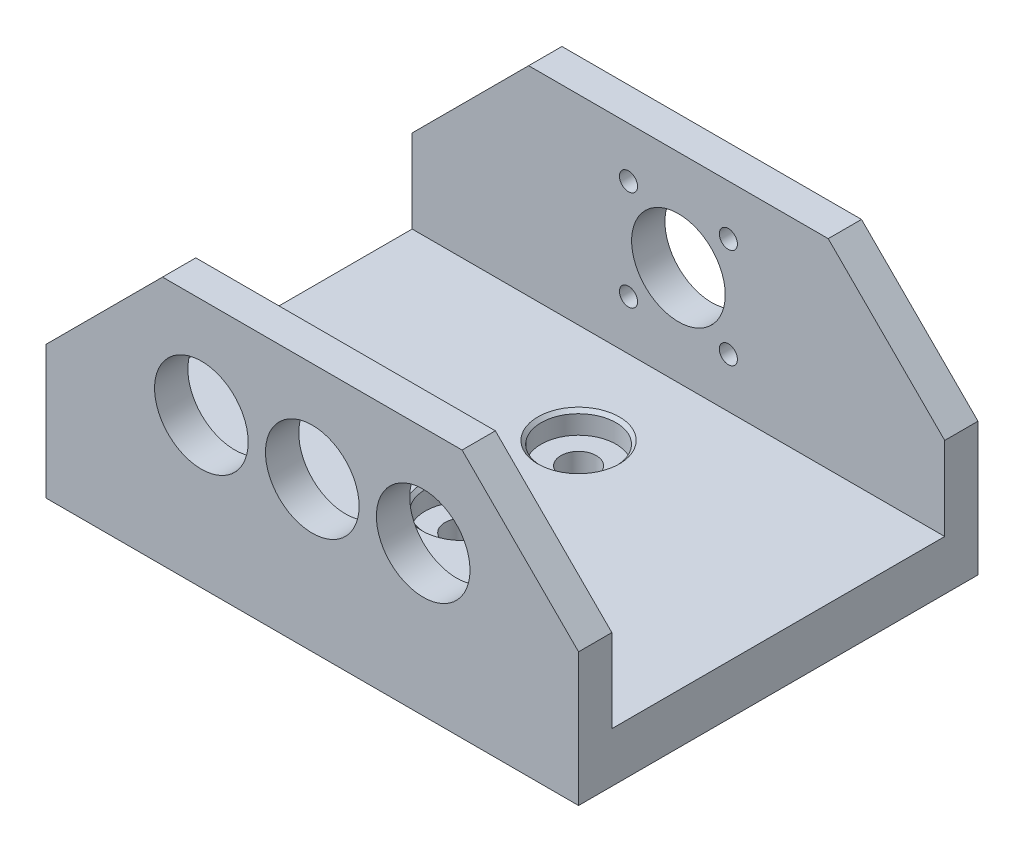
SolidWorks part; units mm, degrees
ref_plane "Front Plane" through (0, 0, 0) normal (0, 0, 1) x (1, 0, 0)
ref_plane "Top Plane" through (0, 0, 0) normal (0, 1, 0) x (1, 0, 0)
ref_plane "Right Plane" through (0, 0, 0) normal (1, 0, 0) x (0, 0, -1)
sketch "Sketch1" plane through (0, 0, 0) normal (0, 1, 0) x (1, 0, 0)
  line L1 (0, 0) -> (101.6, 0)
  line L2 (0, 0) -> (0, 76.2)
  line L3 (0, 76.2) -> (101.6, 76.2)
  line L4 (101.6, 0) -> (101.6, 76.2)
  dimension "D1" = 76.2
  dimension "D2" = 101.6
extrude "Boss-Extrude1" add sketch "Sketch1" along normal blind 50.8 contours L3 L4 L1 L2
ref_plane "Plane1" through (0, 0, -38.1) normal (0, 0, 1) x (1, 0, 0)
sketch "Sketch9" plane through (0, 0, -38.1) normal (0, 0, 1) x (1, 0, 0)
  line L0 (0, 50.8) -> (101.6, 50.8) construction
  line L1 (0, 50.8) -> (101.6, 50.8)
  line L2 (50.8, 50.8) -> (50.8, 0) construction
  line L3 (0, 50.8) -> (0, 9.525)
  line L4 (0, 9.525) -> (101.6, 9.525)
  line L5 (101.6, 50.8) -> (101.6, 9.525)
  line L6 (0, 0) -> (101.6, 0) construction
  line L7 (0, 0) -> (101.6, 0) construction
  point P8 (50.8, 9.525)
  dimension "D1" = 9.525
extrude "Cut-Extrude1" cut sketch "Sketch9" against normal blind 31.75 and the other way blind 31.75
hole_wizard "45/64 (0.70313) Diameter Hole1" positions "Sketch4" profile "Sketch5" hole size "45/64" standard "ANSI Inch" end condition through all
sketch "Sketch4" plane through (0, 0, 0) normal (0, 0, 1) x (1, 0, 0)
  line L1 (0, 28.5242) -> (101.6, 28.5242) construction
  line L2 (0, 50.8) -> (0, 0) construction
  line L3 (101.6, 50.8) -> (101.6, 0) construction
  line L5 (0, 9.525) -> (101.6, 9.525) construction
  line L6 (0, 9.525) -> (101.6, 9.525) construction
  point P7 (50.8, 28.5242)
  point P16 (50.8, 28.5242)
  dimension "D1" = 18.9992
sketch "Sketch5" plane through (50.8, 28.5242, 0) normal (1, 0, 0) x (0, -1, 0)
  line L0 (0, 0) -> (0, 76.2)
  line L1 (0, 76.2) -> (8.9298, 76.2)
  line L2 (8.9298, 76.2) -> (8.9298, 0)
  line L5 (8.9298, 0) -> (0, 0)
  line L11 (0, -6.35) -> (0, 107.95) construction
  dimension "Thru Hole Dia." = 17.8595
  dimension "Thru Hole Depth" = 76.2
hole_wizard "45/64 (0.70313) Diameter Hole2" positions "Sketch7" profile "Sketch6" hole size "45/64" standard "ANSI Inch"
sketch "Sketch7" plane through (0, 0, 0) normal (0, 0, 1) x (1, 0, 0)
  line L2 (0, 28.5242) -> (152.4, 28.5242) construction
  line L5 (50.8, 28.5242) -> (50.8, 0) construction
  line L6 (0, 0) -> (101.6, 0) construction
  circle A1 centre (50.8, 28.5242) radius 8.9298 construction
  point P0 (29.6418, 28.5242)
  point P2 (71.9582, 28.5242)
  dimension "D1" = 21.1582
  dimension "D2" = 21.1582
sketch "Sketch6" plane through (29.6418, 28.5242, 0) normal (1, 0, 0) x (0, -1, 0)
  line L0 (0, 0) -> (0, 30.7655)
  line L1 (0, 30.7655) -> (8.9298, 25.4)
  line L2 (8.9298, 25.4) -> (8.9298, 0)
  line L5 (8.9298, 0) -> (0, 0)
  line L10 (0, 30.7655) -> (-8.9298, 25.4) construction
  line L11 (0, -6.35) -> (0, 107.95) construction
  dimension "Hole Dia." = 17.8595
  dimension "Hole Depth" = 25.4
  dimension "Drill Angle" = 118
hole_wizard "CBORE for 1/4 Binding Head Machine Screw1" positions "Sketch13" profile "Sketch14" counterbore size "1/4" standard "ANSI Inch" end condition through all
sketch "Sketch13" plane through (0, 9.525, 0) normal (0, 1, 0) x (1, 0, 0)
  line L0 (50.8, 69.85) -> (50.8, 6.35) construction
  line L1 (0, 69.85) -> (101.6, 69.85) construction
  line L2 (0, 6.35) -> (101.6, 6.35) construction
  line L3 (0, 76.2) -> (101.6, 76.2) construction
  line L4 (0, 76.2) -> (101.6, 76.2) construction
  point P9 (50.8, 50.8)
  point P11 (50.8, 28.702)
  dimension "D1" = 22.098
  dimension "D2" = 25.4
sketch "Sketch14" plane through (50.8, 9.525, -50.8) normal (1, 0, 0) x (0, 0, 1)
  line L0 (0, 0) -> (0, 9.525)
  line L1 (0, 9.525) -> (3.3782, 9.525)
  line L3 (3.3782, 9.525) -> (3.3782, 4.191)
  line L4 (7.1437, 4.191) -> (3.3782, 4.191)
  line L5 (7.1437, 4.191) -> (7.1438, 0.635)
  line L6 (7.1438, 0.635) -> (7.7788, 0)
  line L7 (7.7788, 0) -> (0, 0)
  line L8 (-7.1438, 0.635) -> (-7.7788, 0) construction
  line L11 (0, -6.35) -> (0, 107.95) construction
  dimension "Thru Hole Dia." = 6.7564
  dimension "Thru Hole Depth" = 9.525
  dimension "C'Bore Dia." = 14.2875
  dimension "C'Bore Depth" = 4.191
  dimension "Near C'Sink Dia." = 15.5575
  dimension "Near C'Sink Angle" = 90
sketch "Sketch17" plane through (0, 0, 0) normal (0, 0, 1) x (1, 0, 0)
  line L0 (0, 25.4) -> (22.225, 47.625)
  line L1 (0, 50.8) -> (0, 0) construction
  line L2 (22.225, 47.625) -> (79.375, 47.625)
  line L3 (79.375, 47.625) -> (101.6, 25.4)
  line L4 (101.6, 50.8) -> (101.6, 0) construction
  line L5 (0, 25.4) -> (0, 50.8)
  line L6 (0, 50.8) -> (101.6, 50.8)
  line L7 (101.6, 50.8) -> (101.6, 25.4)
  dimension "D1" = 3.175
  dimension "D2" = 45
  dimension "D3" = 22.225
extrude "Cut-Extrude3" cut sketch "Sketch17" against normal through all
hole_wizard "#8-32 Tapped Hole1" positions "Sketch19" profile "Sketch20" tap size "#8-32" standard "ANSI Inch"
sketch "Sketch19" plane through (0, 0, -76.2) normal (0, 0, -1) x (-1, 0, 0)
  line L1 (-60.325, 18.9992) -> (-41.275, 18.9992) construction
  line L2 (-60.325, 18.9992) -> (-60.325, 38.0492) construction
  line L3 (-60.325, 38.0492) -> (-41.275, 38.0492) construction
  line L4 (-41.275, 18.9992) -> (-41.275, 38.0492) construction
  line L5 (-60.325, 18.9992) -> (-41.275, 38.0492) construction
  line L6 (-60.325, 38.0492) -> (-41.275, 18.9992) construction
  circle A0 centre (-50.8, 28.5242) radius 19.05 construction
  point P5 (-41.275, 38.0492)
  point P112 (-60.325, 18.9992)
  point P113 (-60.325, 38.0492)
  point P114 (-41.275, 18.9992)
  dimension "D1" = 38.1
  dimension "D2" = 19.05
sketch "Sketch20" plane through (41.275, 38.0492, -76.2) normal (1, 0, 0) x (0, 1, 0)
  line L0 (0, 0) -> (0, 6.35)
  line L1 (0, 6.35) -> (1.7272, 6.35)
  line L2 (1.7272, 6.35) -> (1.7272, 0)
  line L5 (1.7272, 0) -> (0, 0)
  line L11 (0, -6.35) -> (0, 107.95) construction
  dimension "Thru Tap Drill Dia." = 3.4544
  dimension "Thru Tap Drill Depth" = 6.35
cosmetic thread "Hole Thread1" parameters "D2"=4.1656
cosmetic thread "Hole Thread2" parameters "D2"=4.1656
cosmetic thread "Hole Thread3" parameters "D2"=4.1656
cosmetic thread "Hole Thread4" parameters "D2"=4.1656
